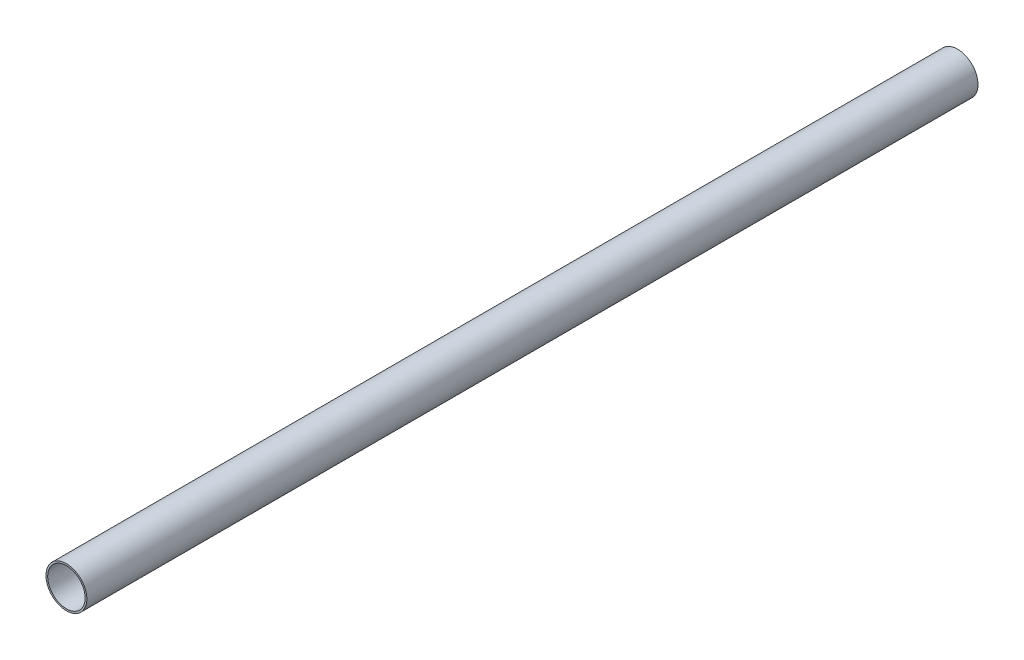
SolidWorks part; units mm, degrees
material "PC High Viscosity"
ref_plane "Front Plane" through (0, 0, 0) normal (0, 0, 1) x (1, 0, 0)
ref_plane "Top Plane" through (0, 0, 0) normal (0, 1, 0) x (1, 0, 0)
ref_plane "Right Plane" through (0, 0, 0) normal (1, 0, 0) x (0, 0, -1)
sketch "Sketch1" plane through (0, 0, 0) normal (0, 0, 1) x (1, 0, 0)
  circle A0 centre (0, 0) radius 12.7
  circle A1 centre (0, 0) radius 11.6205
  dimension "D1" = 25.4
  dimension "D2" = 23.241
extrude "Boss-Extrude1" add sketch "Sketch1" along normal blind 553.63
